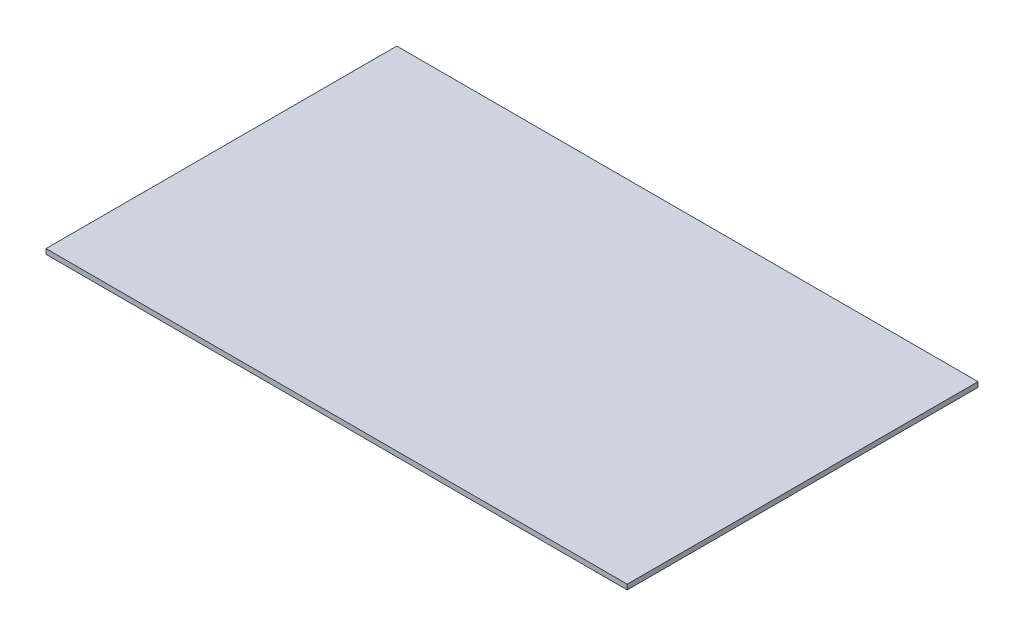
SolidWorks part; units mm, degrees
material "PVC 0.007 Plasticized"
ref_plane "Front Plane" through (0, 0, 0) normal (0, 0, 1) x (1, 0, 0)
ref_plane "Top Plane" through (0, 0, 0) normal (0, 1, 0) x (1, 0, 0)
ref_plane "Right Plane" through (0, 0, 0) normal (1, 0, 0) x (0, 0, -1)
sketch "Sketch1" plane through (0, 0, 0) normal (0, 1, 0) x (1, 0, 0)
  line L1 (0, 0) -> (116, 0)
  line L2 (0, 0) -> (0, 70)
  line L3 (0, 70) -> (116, 70)
  line L4 (116, 0) -> (116, 70)
  dimension "D1" = 116
  dimension "D2" = 70
extrude "Boss-Extrude1" add sketch "Sketch1" along normal blind 1
